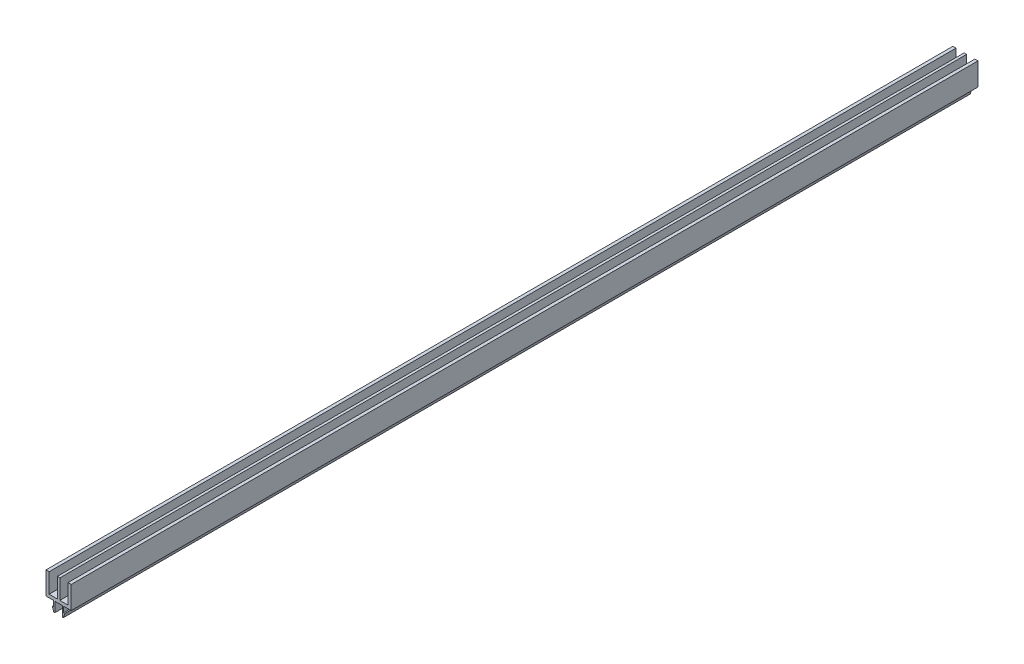
SolidWorks part; units mm, degrees
ref_plane "Plan de face" through (0, 0, 0) normal (0, 0, 1) x (1, 0, 0)
ref_plane "Plan de dessus" through (0, 0, 0) normal (0, 1, 0) x (1, 0, 0)
ref_plane "Plan de droite" through (0, 0, 0) normal (1, 0, 0) x (0, 0, -1)
ref_plane "Plan1" through (0, 0, 50) normal (0, 0, 1) x (1, 0, 0)
sketch "Esquisse1" plane through (0, 0, 50) normal (0, 0, 1) x (1, 0, 0)
  line L0 (-1, 2.5) -> (-7.5, 2.5)
  line L1 (-7.5, 2.5) -> (-7.5, 18)
  line L2 (-7.5, 18) -> (-10, 18)
  line L3 (-10, 18) -> (-10, 0)
  line L4 (-10, 0) -> (-4, 0)
  line L5 (-4, 0) -> (-4, -4.5)
  line L6 (-4, -4.5) -> (-5, -4.5)
  line L7 (-5, -4.5) -> (-3.75, -8)
  line L8 (-3.75, -8) -> (-3, -8)
  line L9 (-3, -8) -> (-3, 0)
  line L10 (-3, 0) -> (3, 0)
  line L11 (3, 0) -> (3, -8)
  line L12 (3, -8) -> (3.75, -8)
  line L13 (3.75, -8) -> (5, -4.5)
  line L14 (5, -4.5) -> (4, -4.5)
  line L15 (4, -4.5) -> (4, 0)
  line L16 (4, 0) -> (10, 0)
  line L17 (10, 0) -> (10, 18)
  line L18 (10, 18) -> (7.5, 18)
  line L19 (7.5, 18) -> (7.5, 2.5)
  line L20 (7.5, 2.5) -> (1, 2.5)
  line L21 (1, 2.5) -> (1, 18)
  line L22 (1, 18) -> (-1, 18)
  line L23 (-1, 18) -> (-1, 2.5)
extrude "Boss.-Extru.1" add sketch "Esquisse1" against normal blind 720
